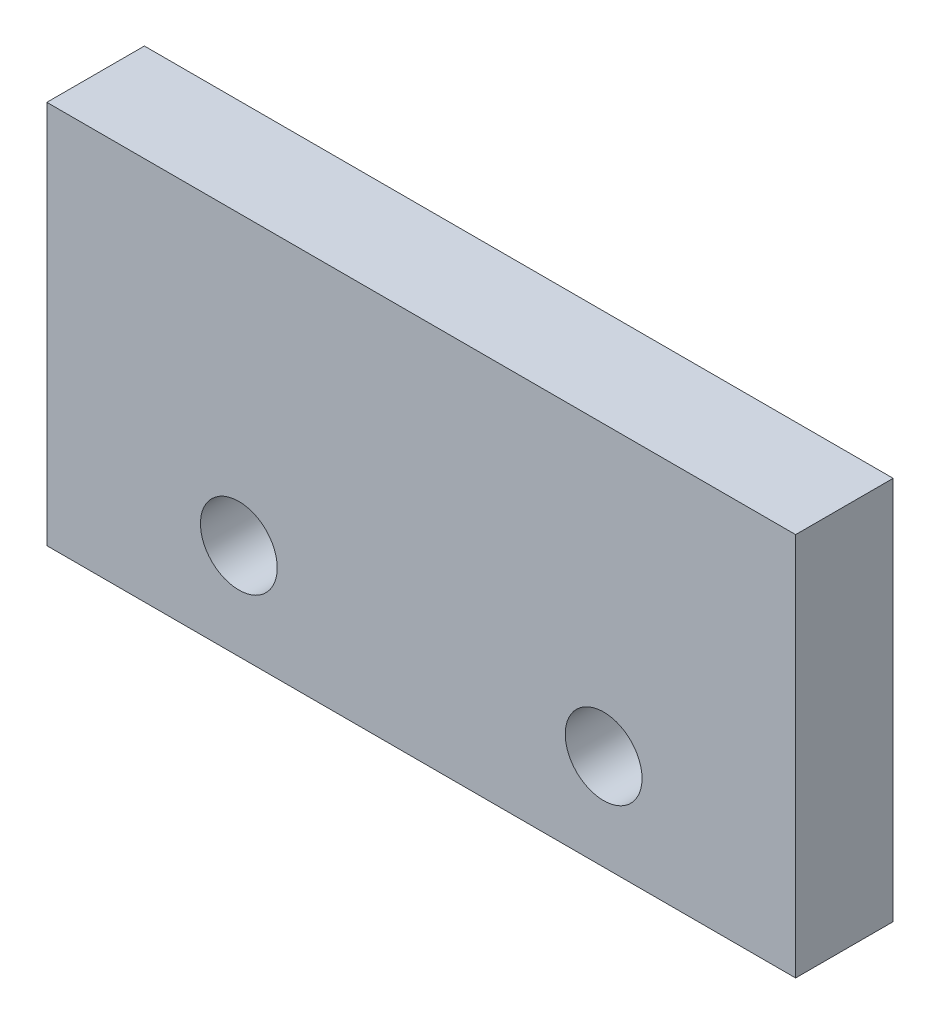
SolidWorks part; units mm, degrees
material "PLA"
ref_plane "Front Plane" through (0, 0, 0) normal (0, 0, 1) x (1, 0, 0)
ref_plane "Top Plane" through (0, 0, 0) normal (0, 1, 0) x (1, 0, 0)
ref_plane "Right Plane" through (0, 0, 0) normal (1, 0, 0) x (0, 0, -1)
sketch "Sketch2" plane through (0, 0, 0) normal (0, 0, 1) x (1, 0, 0)
  line L0 (-4.75, -2.5) -> (4.75, -2.5) construction
  line L1 (-9.75, -5) -> (9.75, -5)
  line L2 (-9.75, -5) -> (-9.75, 5)
  line L3 (-9.75, 5) -> (9.75, 5)
  line L4 (9.75, -5) -> (9.75, 5)
  line L5 (-9.75, -5) -> (9.75, 5) construction
  line L6 (-9.75, 5) -> (9.75, -5) construction
  circle A0 centre (-4.75, -2.5) radius 1
  circle A1 centre (4.75, -2.5) radius 1
  point P0 (0, 0)
  point P10 (0, 0)
  dimension "D6" = 2
  dimension "D1" = 19.5
  dimension "D2" = 10
  dimension "D3" = 5
  dimension "D4" = 5
  dimension "D5" = 2.5
extrude "Boss-Extrude1" add sketch "Sketch2" along normal mid plane 2.54
